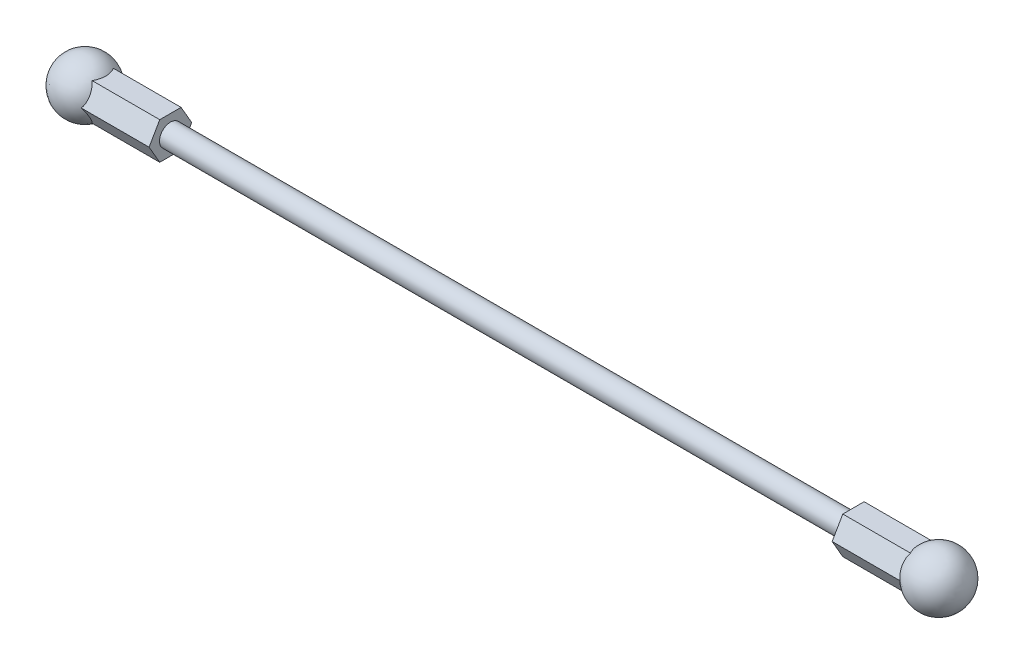
SolidWorks part; units mm, degrees
ref_plane "Front Plane" through (0, 0, 0) normal (0, 0, 1) x (1, 0, 0)
ref_plane "Top Plane" through (0, 0, 0) normal (0, 1, 0) x (1, 0, 0)
ref_plane "Right Plane" through (0, 0, 0) normal (1, 0, 0) x (0, 0, -1)
sketch "Sketch2" plane through (0, 0, 0) normal (0, 0, 1) x (1, 0, 0)
  line L5 (0, 3) -> (0, -3)
  arc A0 (0, 3) -> (0, -3) centre (0, 0) cw
  dimension "D3" = 3
revolve "Revolve1" add sketch "Sketch2" angle 360 about L5
ref_point "Point1"
ref_plane "Plane3" through (92.5, 0, 0) normal (1, 0, 0) x (0, 0, -1)
sketch "Sketch7" plane through (92.5, 0, 0) normal (1, 0, 0) x (0, 0, -1)
  line L0 (0, 3) -> (0, -3)
  circle A0 centre (0, 0) radius 3 construction
  arc A1 (0, 3) -> (0, -3) centre (0, 0) cw
revolve "Revolve2" add sketch "Sketch7" angle 360 about L0
ref_point "Point2"
sketch "Sketch3" plane through (0, 0, 0) normal (1, 0, 0) x (0, 0, -1)
  line L1 (1.1547, -2) -> (2.3094, 0)
  line L2 (2.3094, 0) -> (1.1547, 2)
  line L3 (1.1547, 2) -> (-1.1547, 2)
  line L4 (-1.1547, 2) -> (-2.3094, 0)
  line L5 (-2.3094, 0) -> (-1.1547, -2)
  line L6 (-1.1547, -2) -> (1.1547, -2)
  circle A0 centre (0, 0) radius 2 construction
  dimension "D1" = 4
extrude "Boss-Extrude2" add sketch "Sketch3" along normal blind 9.25 contours L4 L5 L6 L1 L2 L3
ref_plane "Plane4" through (46.25, 0, 0) normal (1, 0, 0) x (0, 0, -1)
mirror "Mirror3" about plane through (46.25, 0, 0) normal (1, 0, 0) of "Boss-Extrude2"
sketch "Sketch5" plane through (9.25, 0, 0) normal (1, 0, 0) x (0, 0, -1)
  line L0 (-2.3094, 0) -> (-1.1827, 0) construction
  circle A0 centre (0.0079, 0) radius 1.1906
  dimension "D1" = 2.3813
extrude "Boss-Extrude3" add sketch "Sketch5" along normal up to surface (74 mm away) up to face at (83.25, 0, 0)
